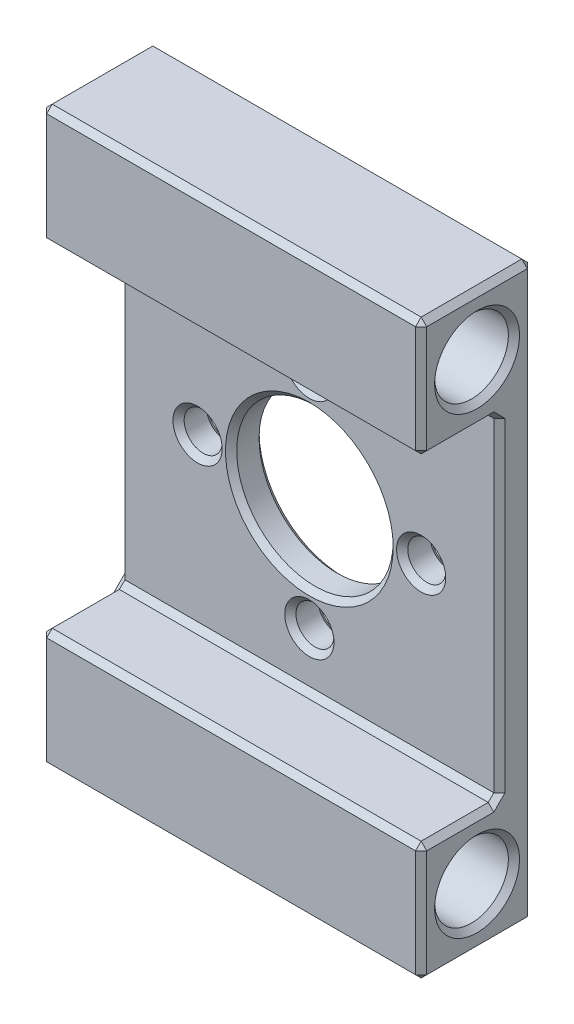
SolidWorks part; units mm, degrees
ref_plane "Plan de face" through (0, 0, 0) normal (0, 0, 1) x (1, 0, 0)
ref_plane "Plan de dessus" through (0, 0, 0) normal (0, 1, 0) x (1, 0, 0)
ref_plane "Plan de droite" through (0, 0, 0) normal (1, 0, 0) x (0, 0, -1)
sketch "Esquisse1" plane through (0, 0, 0) normal (0, 0, 1) x (1, 0, 0)
  line L1 (0, 0) -> (34, 0)
  line L2 (0, 0) -> (0, 51.2)
  line L3 (0, 51.2) -> (34, 51.2)
  line L4 (34, 0) -> (34, 51.2)
  dimension "D1" = 51.2
  dimension "D2" = 34
extrude "Boss.-Extru.1" add sketch "Esquisse1" along normal blind 10
sketch "Esquisse4" plane through (0, 0, 10) normal (0, 0, 1) x (1, 0, 0)
  line L0 (34, 51.2) -> (0, 0) construction
  line L1 (0, 51.2) -> (0, 0) construction
  line L2 (0, 40.6) -> (34, 40.6)
  line L3 (0, 40.6) -> (0, 10.6)
  line L4 (0, 10.6) -> (34, 10.6)
  line L5 (34, 40.6) -> (34, 10.6)
  line L6 (34, 0) -> (34, 51.2) construction
  line L7 (34, 40.6) -> (0, 10.6) construction
  point P12 (17, 25.6)
  point P13 (17, 25.6)
  dimension "D1" = 30
extrude "Enlèv. mat.-Extru.1" cut sketch "Esquisse4" against normal blind 7
sketch "Esquisse5" plane through (0, 0, 3) normal (0, 0, 1) x (1, 0, 0)
  line L0 (34, 40.6) -> (0, 10.6) construction
  circle A0 centre (17, 25.6) radius 7
  dimension "D1" = 14
extrude "Enlèv. mat.-Extru.2" cut sketch "Esquisse5" against normal through all
hole_wizard "Dégagement M62" positions "Esquisse6" profile "Esquisse7" hole size "M6" standard "ISO" end condition through all
sketch "Esquisse6" plane through (0, 0, 0) normal (-1, 0, 0) x (0, 0, 1)
  line L0 (10, 10.6) -> (0, 0) construction
  line L2 (10, 40.6) -> (0, 51.2) construction
  point P0 (5, 45.9)
  point P2 (5, 5.3)
sketch "Esquisse7" plane through (0, 45.9, 5) normal (0, 1, 0) x (0, 0, 1)
  line L0 (0, 0) -> (0, 34)
  line L1 (0, 34) -> (3.3, 34)
  line L2 (3.3, 34) -> (3.3, 0)
  line L5 (3.3, 0) -> (0, 0)
  line L11 (0, -6.35) -> (0, 107.95) construction
  dimension "Diamètre du perçage jusqu'au prochain" = 6.6
  dimension "Profondeur du perçage jusqu'au prochain" = 34
hole_wizard "Dégagement M31" positions "Esquisse9" profile "Esquisse10" hole size "M3" standard "ISO" end condition through all
sketch "Esquisse9" plane through (0, 0, 3) normal (0, 0, 1) x (1, 0, 0)
  line L0 (17, 25.6) -> (17, 35.6) construction
  line L2 (17, 25.6) -> (7, 25.6) construction
  line L4 (27, 25.6) -> (17, 25.6) construction
  line L5 (17, 25.6) -> (17, 15.6) construction
  point P0 (17, 35.6)
  point P2 (7, 25.6)
  point P4 (17, 15.6)
  point P6 (27, 25.6)
  dimension "D1" = 90
  dimension "D2" = 90
  dimension "D3" = 90
  dimension "D4" = 10
sketch "Esquisse10" plane through (17, 35.6, 3) normal (1, 0, 0) x (0, -1, 0)
  line L0 (0, 0) -> (0, 3)
  line L1 (0, 3) -> (1.7, 3)
  line L2 (1.7, 3) -> (1.7, 0)
  line L5 (1.7, 0) -> (0, 0)
  line L11 (0, -6.35) -> (0, 107.95) construction
  dimension "Diamètre du perçage jusqu'au prochain" = 3.4
  dimension "Profondeur du perçage jusqu'au prochain" = 3
chamfer "Chanfrein1" distance 0.5 angle 45 38 edges at (0, 0, 5) (34, 0, 5) (34, 51.2, 5) (17, 51.2, 0) (34, 25.6, 0) (17, 0, 0) (0, 25.6, 0) (0, 51.2, 5) (17, 51.2, 10) (34, 5.3, 10) (34, 45.9, 10) (17, 0, 10) (0, 45.9, 10) (0, 5.3, 10) (0, 40.6, 6.5) (17, 40.6, 10) (34, 40.6, 6.5) (34, 10.6, 6.5) (17, 40.6, 3) (34, 25.6, 3) (17, 10.6, 3) (0, 25.6, 3) (0, 10.6, 6.5) (17, 10.6, 10) (24, 25.6, 0) (24, 25.6, 3) (34, 5.3, 8.3) (0, 5.3, 8.3) (34, 45.9, 8.3) (0, 45.9, 8.3) (28.7, 25.6, 0) (28.7, 25.6, 3) (18.7, 15.6, 0) (18.7, 15.6, 3) (8.7, 25.6, 0) (8.7, 25.6, 3) (18.7, 35.6, 0) (18.7, 35.6, 3)
